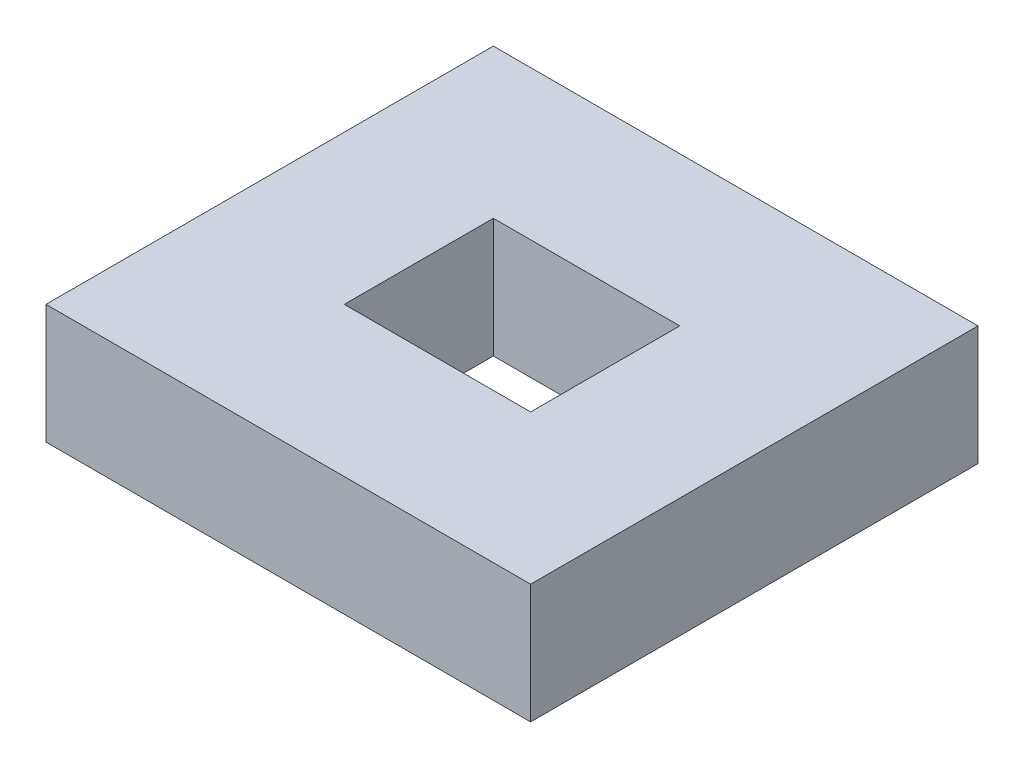
SolidWorks part; units mm, degrees
ref_plane "Front Plane" through (0, 0, 0) normal (0, 0, 1) x (1, 0, 0)
ref_plane "Top Plane" through (0, 0, 0) normal (0, 1, 0) x (1, 0, 0)
ref_plane "Right Plane" through (0, 0, 0) normal (1, 0, 0) x (0, 0, -1)
sketch "Sketch1" plane through (0, 0, 0) normal (0, 1, 0) x (1, 0, 0)
  line L1 (-1.9844, -1.5875) -> (1.9844, -1.5875)
  line L2 (-1.9844, -1.5875) -> (-1.9844, 1.5875)
  line L3 (-1.9844, 1.5875) -> (1.9844, 1.5875)
  line L4 (1.9844, -1.5875) -> (1.9844, 1.5875)
  line L5 (-1.9844, -1.5875) -> (1.9844, 1.5875) construction
  line L6 (-1.9844, 1.5875) -> (1.9844, -1.5875) construction
  line L7 (-5.1594, -4.7625) -> (5.1594, -4.7625)
  line L8 (-5.1594, -4.7625) -> (-5.1594, 4.7625)
  line L9 (-5.1594, 4.7625) -> (5.1594, 4.7625)
  line L10 (5.1594, -4.7625) -> (5.1594, 4.7625)
  line L11 (-5.1594, -4.7625) -> (5.1594, 4.7625) construction
  line L12 (-5.1594, 4.7625) -> (5.1594, -4.7625) construction
  point P0 (0, 0)
  point P6 (0, 0)
  dimension "D1" = 3.175
  dimension "D2" = 3.9688
  dimension "D3" = 3.175
  dimension "D4" = 3.175
extrude "Boss-Extrude1" add sketch "Sketch1" along normal blind 2.54
